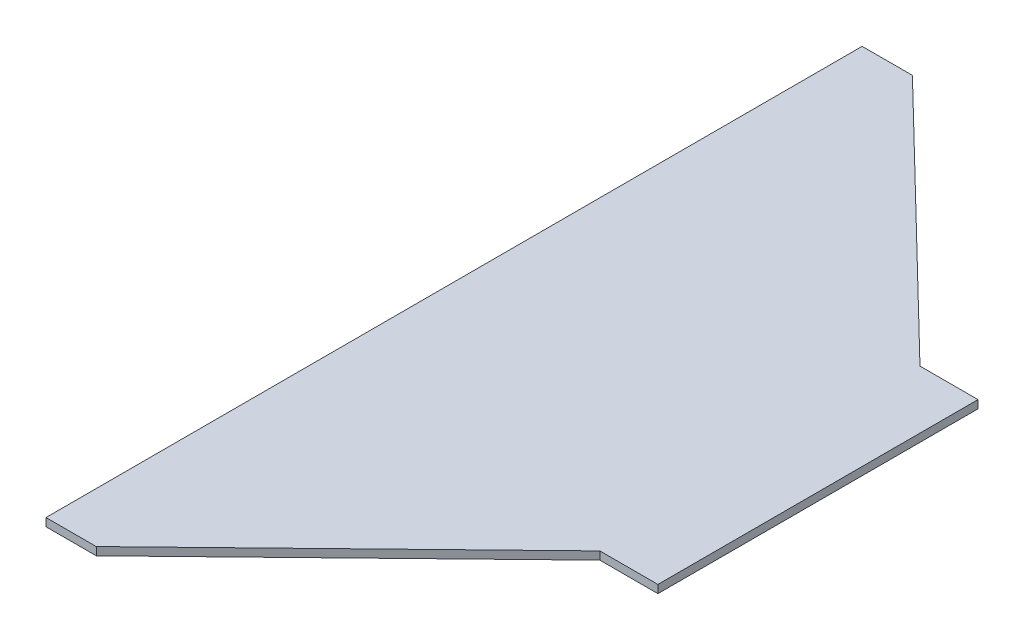
SolidWorks part; units mm, degrees
ref_plane "Front Plane" through (0, 0, 0) normal (0, 0, 1) x (1, 0, 0)
ref_plane "Top Plane" through (0, 0, 0) normal (0, 1, 0) x (1, 0, 0)
ref_plane "Right Plane" through (0, 0, 0) normal (1, 0, 0) x (0, 0, -1)
sketch "Croquis1" plane through (0, 0, 0) normal (0, 1, 0) x (1, 0, 0)
  line L0 (0, 0) -> (0, -101.83)
  line L1 (0, -101.83) -> (6.27, -101.83)
  line L3 (6.27, -101.83) -> (38.16, -70.885)
  line L4 (38.16, -70.885) -> (45.4, -70.885)
  line L5 (45.4, -70.885) -> (45.4, -30.945)
  line L6 (45.4, -30.945) -> (38.16, -30.945)
  line L7 (38.16, -30.945) -> (6.27, 0)
  line L9 (6.27, 0) -> (0, 0)
  point P12 (45.4, -50.915)
  point P13 (0, -50.915)
  dimension "D1" = 6.27
  dimension "D2" = 101.83
  dimension "D3" = 45.4
  dimension "D5" = 7.24
  dimension "D6" = 39.94
extrude "Saliente-Extruir1" add sketch "Croquis1" along normal blind 1
